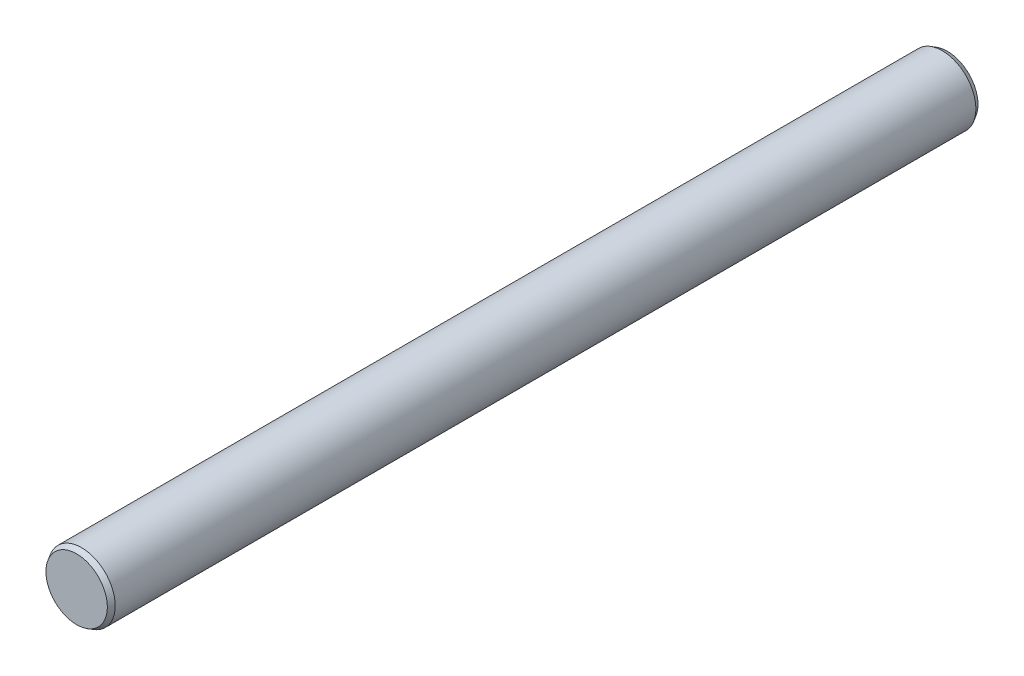
SolidWorks part; units mm, degrees
material "Cast Stainless Steel"
ref_plane "Front" through (0, 0, 0) normal (0, 0, 1) x (1, 0, 0)
ref_plane "Top" through (0, 0, 0) normal (0, 1, 0) x (1, 0, 0)
ref_plane "Right" through (0, 0, 0) normal (1, 0, 0) x (0, 0, -1)
sketch "Sketch2" plane through (0, 0, 0) normal (0, 0, 1) x (1, 0, 0)
  circle A0 centre (0, 0) radius 1.7145
  dimension "D1" = 3.429
extrude "Extrude1" add sketch "Sketch2" along normal mid plane 44.45
chamfer "Chamfer1" distance 0.254 angle 30 2 edges at (1.7145, 0, 22.225) (1.7145, 0, -22.225)
